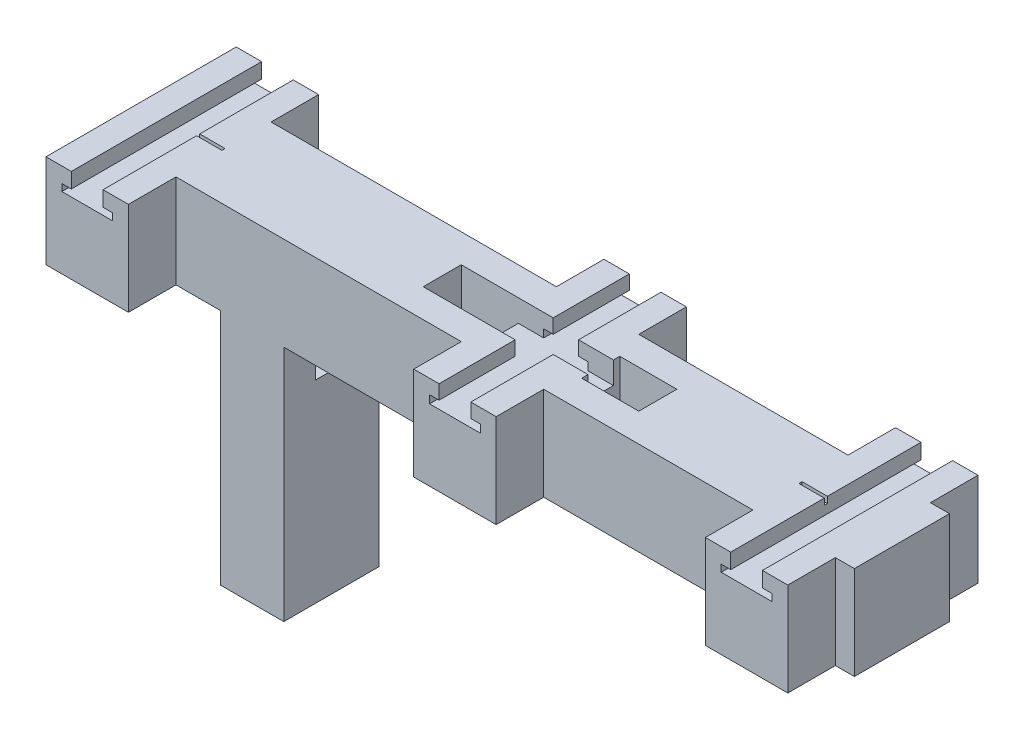
SolidWorks part; units mm, degrees
ref_plane "Front Plane" through (0, 0, 0) normal (0, 0, 1) x (1, 0, 0)
ref_plane "Top Plane" through (0, 0, 0) normal (0, 1, 0) x (1, 0, 0)
ref_plane "Right Plane" through (0, 0, 0) normal (1, 0, 0) x (0, 0, -1)
sketch "Sketch2" plane through (0, 0, 0) normal (0, 1, 0) x (1, 0, 0)
  line L1 (-120, 20) -> (120, 20)
  line L2 (-120, 20) -> (-120, -20)
  line L3 (-120, -20) -> (120, -20)
  line L4 (120, 20) -> (120, -20)
  line L5 (-120, 20) -> (120, -20) construction
  line L6 (-120, -20) -> (120, 20) construction
  point P0 (0, 0)
  dimension "D1" = 240
  dimension "D2" = 40
extrude "Boss-Extrude1" add sketch "Sketch2" along normal blind 15 and the other way blind 22.5
sketch "Sketch3" plane through (0, 0, 20) normal (0, 0, 1) x (1, 0, 0)
  line L0 (22, 0) -> (-22, 0) construction
  line L1 (-115, 0) -> (-99, 0)
  line L2 (-115, 0) -> (-115, 2.2)
  line L3 (-115, 2.2) -> (-99, 2.2)
  line L4 (-99, 0) -> (-99, 2.2)
  line L5 (-120, -22.5) -> (-120, 15) construction
  line L6 (-115, 0) -> (-99, 2.2) construction
  line L7 (-115, 2.2) -> (-99, 0) construction
  line L8 (0.9999, 0) -> (16.9999, 2.5) construction
  line L9 (0.9999, 0) -> (16.9999, 0)
  line L10 (0.9999, 0) -> (0.9999, 2.5)
  line L11 (0.9999, 2.5) -> (16.9999, 2.5)
  line L12 (16.9999, 0) -> (16.9999, 2.5)
  line L13 (16.9999, 0) -> (0.9999, 2.5) construction
  line L14 (92.9998, 0) -> (108.9998, 2.2) construction
  line L15 (92.9998, 0) -> (108.9998, 0)
  line L16 (92.9998, 0) -> (92.9998, 2.2)
  line L17 (92.9998, 2.2) -> (108.9998, 2.2)
  line L18 (108.9998, 0) -> (108.9998, 2.2)
  line L19 (108.9998, 0) -> (92.9998, 2.2) construction
  point P8 (-107, 1.1)
  point P13 (8.9999, 1.25)
  point P18 (100.9998, 1.1)
  dimension "D1" = 5
  dimension "D2" = 16
  dimension "D3" = 2.2
  dimension "D4" = 16
  dimension "D5" = 2.5
  dimension "D6" = 116
  dimension "D7" = 16
  dimension "D8" = 2.2
  dimension "D9" = 92
extrude "Cut-Extrude1" cut sketch "Sketch3" against normal up to next
sketch "Sketch5" plane through (0, 15, 0) normal (0, 1, 0) x (1, 0, 0)
  line L1 (-120, -20) -> (120, -20)
  line L2 (-120, -20) -> (-120, 20)
  line L3 (-120, 20) -> (120, 20)
  line L4 (120, -20) -> (120, 20)
extrude "Cut-Extrude2" cut sketch "Sketch5" against normal blind 8 contours L2 L1 L4 L3
sketch "Sketch6" plane through (0, -22.5, 0) normal (0, -1, 0) x (1, 0, 0)
  line L7 (-120, -20) -> (-120, 20) construction
  line L8 (-80, -15) -> (-60, -15)
  line L9 (-80, -15) -> (-80, 15)
  line L10 (-80, 15) -> (-60, 15)
  line L11 (-60, -15) -> (-60, 15)
  line L12 (120, -20) -> (-120, -20) construction
  dimension "D1" = 40
  dimension "D2" = 20
  dimension "D3" = 5
  dimension "D4" = 30
extrude "Boss-Extrude2" add sketch "Sketch6" along normal blind 75
sketch "Sketch8" plane through (0, 0, 20) normal (0, 0, 1) x (1, 0, 0)
  line L0 (-99, 2.2) -> (-115, 2.2) construction
  line L1 (-112, 2.2) -> (-102, 2.2)
  line L2 (-112, 2.2) -> (-112, 7)
  line L3 (-112, 7) -> (-102, 7)
  line L4 (-102, 2.2) -> (-102, 7)
  line L5 (-120, 7) -> (120, 7) construction
  line L6 (16.9999, 2.5) -> (0.9999, 2.5) construction
  line L7 (3.9999, 2.5) -> (13.9999, 2.5)
  line L8 (3.9999, 2.5) -> (3.9999, 7)
  line L9 (3.9999, 7) -> (13.9999, 7)
  line L10 (13.9999, 2.5) -> (13.9999, 7)
  line L11 (108.9998, 2.2) -> (92.9998, 2.2) construction
  line L12 (95.9998, 2.2) -> (105.9998, 2.2)
  line L13 (95.9998, 2.2) -> (95.9998, 7)
  line L14 (95.9998, 7) -> (105.9998, 7)
  line L15 (105.9998, 2.2) -> (105.9998, 7)
  dimension "D1" = 3
  dimension "D2" = 10
  dimension "D3" = 10
  dimension "D4" = 3
  dimension "D5" = 10
  dimension "D6" = 3
extrude "Cut-Extrude3" cut sketch "Sketch8" against normal up to next
sketch "Sketch9" plane through (0, 0, 0) normal (0, 1, 0) x (1, 0, 0)
  line L0 (-20.625, 0) -> (20.625, 0) construction
  line L2 (105.9998, 20) -> (105.9998, -20) construction
  line L3 (-102, 20) -> (-102, -20) construction
  circle A0 centre (-107, 0) radius 2.1
  circle A2 centre (100.9998, 0) radius 2.1
  dimension "D1" = 4.2
  dimension "D3" = 4.2
  dimension "D5" = 5
  dimension "D6" = 5
extrude "Cut-Extrude4" cut sketch "Sketch9" against normal blind 4.4
sketch "Sketch10" plane through (0, -4.4, 0) normal (0, 1, 0) x (1, 0, 0)
  circle A0 centre (-107, 0) radius 1.55
  dimension "D1" = 3.1
sketch "Sketch11" plane through (0, -4.4, 0) normal (0, 1, 0) x (1, 0, 0)
  circle A0 centre (100.9998, 0) radius 1.55
  dimension "D1" = 3.1
extrude "Cut-Extrude5" cut sketch "Sketch11" against normal blind 11
extrude "Cut-Extrude6" cut sketch "Sketch10" against normal blind 11
sketch "Sketch12" plane through (0, 0, 0) normal (0, 1, 0) x (1, 0, 0)
  line L0 (-20.625, 0) -> (20.625, 0) construction
  line L1 (4.9999, 4) -> (12.9999, 4)
  line L2 (4.9999, 4) -> (4.9999, -4)
  line L3 (4.9999, -4) -> (12.9999, -4)
  line L4 (12.9999, 4) -> (12.9999, -4)
  line L5 (4.9999, 4) -> (12.9999, -4) construction
  line L6 (4.9999, -4) -> (12.9999, 4) construction
  line L7 (3.9999, 20) -> (3.9999, -20) construction
  circle A0 centre (10.7152, -11.8139) radius 2.1
  circle A1 centre (10.75, 12) radius 2.1
  point P0 (8.9999, 0)
  point P13 (8.9999, -4)
  dimension "D4" = 4.2
  dimension "D5" = 8
  dimension "D1" = 8
  dimension "D2" = 8
  dimension "D3" = 1
  dimension "D6" = 8
extrude "Cut-Extrude7" cut sketch "Sketch12" against normal blind 4.4 contours A0 | A1
sketch "Sketch13" plane through (0, -4.4, 0) normal (0, 1, 0) x (1, 0, 0)
  circle A0 centre (10.7152, -11.8139) radius 1.65
  circle A1 centre (10.75, 12) radius 1.65
  dimension "D1" = 3.3
  dimension "D2" = 3.3
extrude "Cut-Extrude8" cut sketch "Sketch13" against normal blind 11
sketch "Sketch14" plane through (0, 7, 0) normal (0, 1, 0) x (1, 0, 0)
  line L0 (-20.625, 0) -> (20.625, 0) construction
  line L1 (-25.0001, 6) -> (-7.0001, 6)
  line L2 (-25.0001, 6) -> (-25.0001, -6)
  line L3 (-25.0001, -6) -> (-7.0001, -6)
  line L4 (-7.0001, 6) -> (-7.0001, -6)
  line L5 (-25.0001, 6) -> (-7.0001, -6) construction
  line L6 (-25.0001, -6) -> (-7.0001, 6) construction
  line L7 (3.9999, 20) -> (3.9999, -20) construction
  line L8 (8.9999, 20) -> (8.9999, -20) construction
  line L9 (0.9999, 20) -> (16.9999, 20) construction
  line L10 (0.9999, -20) -> (16.9999, -20) construction
  line L11 (42.9999, -6) -> (24.9999, 6) construction
  line L12 (42.9999, 6) -> (24.9999, -6) construction
  line L13 (24.9999, 6) -> (24.9999, -6)
  line L14 (42.9999, -6) -> (24.9999, -6)
  line L15 (42.9999, 6) -> (42.9999, -6)
  line L16 (42.9999, 6) -> (24.9999, 6)
  point P0 (-16.0001, 0)
  point P18 (33.9999, 0)
  dimension "D1" = 18
  dimension "D2" = 20
  dimension "D3" = 12
extrude "Cut-Extrude9" cut sketch "Sketch14" against normal up to surface (29.5 mm away) up to face at (0, -22.5, 0)
sketch "Sketch15" plane through (-80, 0, 0) normal (-1, 0, 0) x (0, 0, 1)
  line L0 (-20, -22.5) -> (20, -22.5) construction
  line L1 (-5, -22.5) -> (5, -22.5)
  line L2 (-5, -22.5) -> (-5, -36.5)
  line L3 (-5, -36.5) -> (5, -36.5)
  line L4 (5, -22.5) -> (5, -36.5)
  line L5 (-5, -22.5) -> (5, -36.5) construction
  line L6 (-5, -36.5) -> (5, -22.5) construction
  line L9 (-15, -97.5) -> (-15, -22.5) construction
  point P4 (0, -29.5)
  dimension "D1" = 10
  dimension "D2" = 14
  dimension "D3" = 10
extrude "Cut-Extrude10" cut sketch "Sketch15" against normal up to surface (20 mm away) up to face at (-60, -60, 0)
sketch "Sketch16" [suppressed] plane through (0, 0, 20) normal (0, 0, 1) x (1, 0, 0)
  line L0 (-95.5, 0) -> (-95.5, 2.5) construction
  line L1 (-77.25, -6.25) -> (-17.25, -6.25)
  line L2 (-77.25, -6.25) -> (-77.25, -16.25)
  line L3 (-77.25, -16.25) -> (-17.25, -16.25)
  line L4 (-17.25, -6.25) -> (-17.25, -16.25)
  line L5 (-77.25, -6.25) -> (-17.25, -16.25) construction
  line L6 (-77.25, -16.25) -> (-17.25, -6.25) construction
  line L7 (-120, -22.5) -> (120, -22.5) construction
  point P4 (-47.25, -11.25)
  dimension "D1" = 60
  dimension "D2" = 10
  dimension "D3" = 18.25
  dimension "D4" = 6.25
sketch "Sketch17" plane through (0, 0, 20) normal (0, 0, 1) x (1, 0, 0)
  line L0 (-120, 7) -> (-120, -22.5)
  line L1 (-120, 7) -> (-112, 7) construction
  line L2 (-120, -22.5) -> (120, -22.5) construction
  line L3 (-94, 7) -> (-94, -22.5)
  line L4 (-102, 7) -> (3.9999, 7) construction
  line L5 (-115, 2.2) -> (-115, 0) construction
  line L6 (-99, 0) -> (-99, 2.2) construction
  line L7 (-120, -22.5) -> (-94, -22.5)
  line L8 (-120, 7) -> (-112, 7)
  line L9 (-112, 7) -> (-112, 2.2)
  line L10 (-112, 2.2) -> (-115, 2.2)
  line L11 (-115, 2.2) -> (-115, 0)
  line L12 (22, 0) -> (-22, 0) construction
  line L13 (-115, 0) -> (-99, 0)
  line L14 (-99, 0) -> (-99, 2.2)
  line L15 (-99, 2.2) -> (-102, 2.2)
  line L16 (-99, 2.2) -> (-102, 2.2) construction
  line L17 (-102, 2.2) -> (-102, 7) construction
  line L18 (-102, 2.2) -> (-102, 7)
  line L19 (-102, 7) -> (-94, 7)
  line L20 (21.9999, 7) -> (21.9999, -22.5)
  line L21 (13.9999, 7) -> (95.9998, 7) construction
  line L22 (-4.0001, 7) -> (-4.0001, -22.5)
  line L23 (0.9999, 2.5) -> (0.9999, 0) construction
  line L24 (16.9999, 0) -> (16.9999, 2.5) construction
  line L25 (-4.0001, 7) -> (3.9999, 7)
  line L26 (3.9999, 7) -> (3.9999, 2.5)
  line L27 (3.9999, 2.5) -> (0.9999, 2.5)
  line L28 (0.9999, 2.5) -> (0.9999, 0)
  line L29 (0.9999, 0) -> (16.9999, 0)
  line L30 (16.9999, 0) -> (16.9999, 2.5)
  line L31 (16.9999, 2.5) -> (13.9999, 2.5)
  line L32 (13.9999, 2.5) -> (13.9999, 7)
  line L33 (13.9999, 7) -> (21.9999, 7)
  line L34 (-4.0001, -22.5) -> (21.9999, -22.5)
  line L35 (87.9998, 7) -> (87.9998, -22.5)
  line L36 (113.9998, 7) -> (113.9998, -22.5)
  line L37 (105.9998, 7) -> (120, 7) construction
  line L38 (92.9998, 2.2) -> (92.9998, 0) construction
  line L39 (108.9998, 0) -> (108.9998, 2.2) construction
  line L40 (87.9998, 7) -> (95.9998, 7)
  line L41 (95.9998, 7) -> (95.9998, 2.2)
  line L42 (95.9998, 2.2) -> (92.9998, 2.2)
  line L43 (92.9998, 2.2) -> (92.9998, 0)
  line L44 (92.9998, 0) -> (108.9998, 0)
  line L45 (108.9998, 0) -> (108.9998, 2.2)
  line L46 (108.9998, 2.2) -> (105.9998, 2.2)
  line L47 (105.9998, 2.2) -> (105.9998, 7)
  line L48 (105.9998, 7) -> (113.9998, 7)
  line L49 (113.9998, -22.5) -> (87.9998, -22.5)
  dimension "D1" = 5
  dimension "D2" = 5
  dimension "D3" = 5
  dimension "D4" = 5
  dimension "D5" = 5
  dimension "D6" = 5
extrude "Boss-Extrude3" add sketch "Sketch17" along normal blind 10 and the other way offset from surface (50 mm away) 10 other way up to face at (0.8571, 1.3786, -20)
sketch "Sketch18" plane through (0, 7, 0) normal (0, 1, 0) x (1, 0, 0)
  line L0 (-94, -15) -> (-4.0001, -15)
  line L1 (113.9998, -15) -> (120, -15)
  line L2 (120, -20) -> (120, 20) construction
  line L3 (-94, 15) -> (-4.0001, 15)
  line L4 (-94, 20) -> (-4.0001, 20) construction
  line L5 (-94, -20) -> (-4.0001, -20) construction
  line L6 (-94, -20) -> (-94, -15)
  line L7 (-4.0001, -20) -> (-4.0001, -15)
  line L8 (21.9999, -20) -> (21.9999, -15)
  line L9 (87.9998, -20) -> (87.9998, -15)
  line L10 (113.9998, -20) -> (113.9998, -15)
  line L11 (113.9998, 20) -> (113.9998, 15)
  line L12 (21.9999, 20) -> (21.9999, 15)
  line L13 (-94, 20) -> (-94, 15)
  line L14 (-4.0001, 20) -> (-4.0001, 15)
  line L15 (21.9999, 15) -> (87.9998, 15)
  line L16 (21.9999, -15) -> (87.9998, -15)
  line L17 (87.9998, 20) -> (87.9998, 15)
  line L18 (113.9998, 15) -> (120, 15)
  line L19 (113.9998, 20) -> (120, 20) construction
  line L20 (113.9998, -20) -> (120, -20) construction
  line L21 (21.9999, 20) -> (87.9998, 20) construction
  line L22 (21.9999, -20) -> (87.9998, -20) construction
  line L23 (113.9998, 20) -> (120, 20)
  line L24 (120, -20) -> (120, -15)
  line L25 (113.9998, -20) -> (120, -20)
  line L26 (21.9999, 20) -> (87.9998, 20)
  line L27 (21.9999, -20) -> (87.9998, -20)
  line L28 (-94, 20) -> (-4.0001, 20)
  line L29 (-94, -20) -> (-4.0001, -20)
  line L30 (120, 15) -> (120, 20)
  point P12 (-49, -20)
  dimension "D1" = 5
  dimension "D2" = 5
extrude "Cut-Extrude11" cut sketch "Sketch18" against normal up to next
sketch "Sketch20" plane through (0, 7, 0) normal (0, 1, 0) x (1, 0, 0)
  line L0 (3.9999, 30) -> (3.9999, -30) construction
  line L2 (3.9999, 6) -> (-7.0001, 6)
  line L10 (3.9999, 6) -> (3.9999, -6)
  line L11 (3.9999, -6) -> (-7.0001, -6)
  line L12 (-7.0001, 6) -> (-7.0001, -6)
  line L13 (-1.5001, -6) -> (-1.5001, 6) construction
  line L14 (3.9999, 0) -> (-7.0001, 0) construction
  line L15 (-7.0001, -6) -> (-7.0001, 6) construction
  line L16 (3.9999, -30) -> (-4.0001, -30) construction
  point P220 (-1.5001, 0)
  dimension "D1" = 24
  dimension "D2" = 12
extrude "Cut-Extrude12" cut sketch "Sketch20" against normal up to surface (7 mm away)
sketch "Sketch21" plane through (0, 7, 0) normal (0, 1, 0) x (1, 0, 0)
  line L0 (-102, 0) -> (-94, 0)
  line L1 (-102, 30) -> (-102, -30) construction
  line L2 (-20.625, 0) -> (20.625, 0) construction
  line L3 (-94, 0) -> (-94, 0.5)
  line L4 (-94, 0.5) -> (-102, 0.5)
  line L5 (-102, 0.5) -> (-102, 0)
  line L6 (-94, 0) -> (-94, -0.5)
  line L7 (-94, -0.5) -> (-102, -0.5)
  line L8 (-102, -0.5) -> (-102, 0)
  line M14 (-102, 30) -> (-102, -30)
  dimension "D1" = 8
  dimension "D2" = 0.5
  dimension "D3" = 0.5
  dimension "D4" = 0.5
extrude "Cut-Extrude13" cut sketch "Sketch21" against normal blind 2 contours L7 L6 L0 M14 | L3 L4 L0 M14
sketch "Sketch22" plane through (0, 7, 0) normal (0, 1, 0) x (1, 0, 0)
  line L0 (-20.625, 0) -> (20.625, 0) construction
  line L1 (87.9998, 0.5) -> (95.9998, 0.5)
  line L2 (87.9998, 0.5) -> (87.9998, -0.5)
  line L3 (87.9998, -0.5) -> (95.9998, -0.5)
  line L4 (95.9998, 0.5) -> (95.9998, -0.5)
  line L5 (87.9998, 0.5) -> (95.9998, -0.5) construction
  line L6 (87.9998, -0.5) -> (95.9998, 0.5) construction
  line L7 (95.9998, 30) -> (95.9998, -30) construction
  point P0 (91.9998, 0)
  dimension "D1" = 8
  dimension "D2" = 1
extrude "Cut-Extrude14" cut sketch "Sketch22" against normal blind 2
sketch "Sketch23" plane through (0, 7, 0) normal (0, 1, 0) x (1, 0, 0)
  line L0 (13.9999, 30) -> (13.9999, -30) construction
  line L1 (13.9999, 4) -> (27.9999, 4)
  line L2 (13.9999, 4) -> (13.9999, -4)
  line L3 (13.9999, -4) -> (27.9999, -4)
  line L4 (27.9999, 4) -> (27.9999, -4)
  line L5 (20.9999, -4) -> (20.9999, 4) construction
  line L6 (13.9999, 0) -> (27.9999, 0) construction
  line L7 (21.9999, -30) -> (13.9999, -30) construction
  point P604 (20.9999, 0)
  line M14 (13.9999, 30) -> (13.9999, -30)
  line M23 (24.9999, -6) -> (24.9999, 6)
  dimension "D1" = 26
  dimension "D2" = 8
  dimension "D3" = 14
extrude "Cut-Extrude15" cut sketch "Sketch23" against normal up to surface (7 mm away) contours L3 L1 M14 M23 up to face at (2.9999, 0, 0)
equation "\"X\"= 16mm"
equation "\"D2@Sketch3\"=\"X\""
equation "\"D7@Sketch3\"=\"X\""
equation "\"D6@Sketch8\"=(\"X\"-10)/2"
equation "\"D4@Sketch8\"=(\"X\"-10)/2"
equation "\"D1@Sketch8\"=(\"X\"-10)/2"
